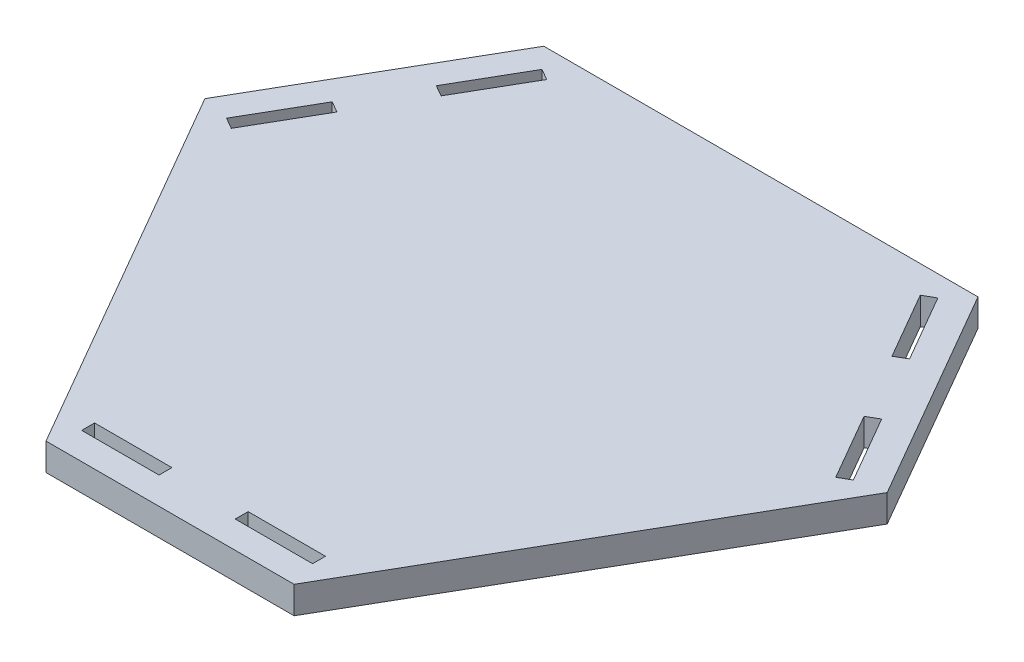
SolidWorks part; units mm, degrees
ref_plane "Front Plane" through (0, 0, 0) normal (0, 0, 1) x (1, 0, 0)
ref_plane "Top Plane" through (0, 0, 0) normal (0, 1, 0) x (1, 0, 0)
ref_plane "Right Plane" through (0, 0, 0) normal (1, 0, 0) x (0, 0, -1)
sketch "Sketch1" plane through (0, 0, 0) normal (0, 1, 0) x (1, 0, 0)
  line L0 (0, 150) -> (-129.9038, -75)
  line L1 (-129.9038, -75) -> (129.9038, -75)
  line L2 (129.9038, -75) -> (0, 150)
  line L4 (0, -125) -> (108.2532, 62.5)
  line L5 (108.2532, 62.5) -> (-108.2532, 62.5)
  line L6 (-108.2532, 62.5) -> (0, -125)
  circle A0 centre (0, 0) radius 150 construction
  circle A1 centre (0, 0) radius 75 construction
  circle A2 centre (0, 0) radius 125 construction
  circle A3 centre (0, 0) radius 62.5 construction
  dimension "D1" = 300
  dimension "D2" = 250
other "AlignGroup1"
extrude "Boss-Extrude1" add sketch "Sketch1" along normal blind 6.35 contours L0 L6 L1 L4 L2 L5
sketch "Sketch2" plane through (0, 6.35, 0) normal (0, 1, 0) x (1, 0, 0)
  line L0 (-28.8675, -75) -> (28.8675, -75) construction
  line L1 (-26.8675, -65.7) -> (-8.8675, -65.7)
  line L2 (-26.8675, -65.7) -> (-26.8675, -68.7)
  line L3 (-26.8675, -68.7) -> (-8.8675, -68.7)
  line L4 (-8.8675, -65.7) -> (-8.8675, -68.7)
  line L5 (0, -75) -> (0, 62.5) construction
  line L6 (50.5181, 62.5) -> (-50.5181, 62.5) construction
  line L7 (26.8675, -65.7) -> (26.8675, -68.7)
  line L8 (-64.9519, 37.5) -> (54.1266, -31.25) construction
  line L9 (-46.0622, 57.6179) -> (-43.4641, 56.1179)
  line L10 (8.8675, -65.7) -> (8.8675, -68.7)
  line L11 (-46.0622, 57.6179) -> (-55.0622, 42.0295)
  line L12 (-55.0622, 42.0295) -> (-52.4641, 40.5295)
  line L13 (26.8675, -68.7) -> (8.8675, -68.7)
  line L14 (26.8675, -65.7) -> (8.8675, -65.7)
  line L15 (-43.4641, 56.1179) -> (-52.4641, 40.5295)
  line L16 (-50.5181, 62.5) -> (-79.3857, 12.5) construction
  line L17 (28.8675, -75) -> (79.3857, 12.5) construction
  line L18 (-70.3316, 9.5821) -> (-61.3316, 25.1705)
  line L19 (-63.9297, 26.6705) -> (-61.3316, 25.1705)
  line L20 (-72.9297, 11.0821) -> (-63.9297, 26.6705)
  line L21 (-72.9297, 11.0821) -> (-70.3316, 9.5821)
  line L22 (64.9519, 37.5) -> (-54.1266, -31.25) construction
  line L23 (79.3857, 12.5) -> (50.5181, 62.5) construction
  line L24 (-79.3857, 12.5) -> (-28.8675, -75) construction
  line L25 (72.9297, 11.0821) -> (63.9297, 26.6705)
  line L26 (43.4641, 56.1179) -> (46.0622, 57.6179)
  line L27 (43.4641, 56.1179) -> (52.4641, 40.5295)
  line L28 (52.4641, 40.5295) -> (55.0622, 42.0295)
  line L29 (46.0622, 57.6179) -> (55.0622, 42.0295)
  line L30 (61.3316, 25.1705) -> (63.9297, 26.6705)
  line L31 (70.3316, 9.5821) -> (61.3316, 25.1705)
  line L32 (70.3316, 9.5821) -> (72.9297, 11.0821)
  point P4 (-17.8675, -68.7)
  dimension "D1" = 18
  dimension "D2" = 3
  dimension "D3" = 6.3
  dimension "D4" = 20
  dimension "D5" = 6.3
  dimension "D6" = 18
  dimension "D7" = 3
  dimension "D8" = 20
  dimension "D9" = 18
  dimension "D10" = 3
  dimension "D11" = 20
  dimension "D12" = 6.3
extrude "Cut-Extrude1" cut sketch "Sketch2" against normal through all
